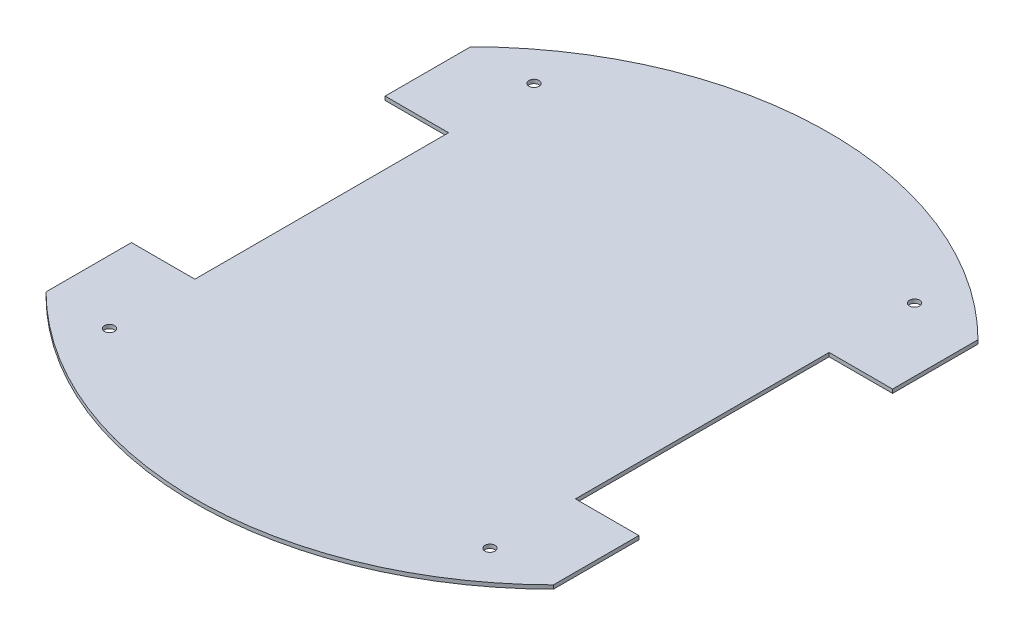
SolidWorks part; units mm, degrees
ref_plane "Front Plane" through (0, 0, 0) normal (0, 0, 1) x (1, 0, 0)
ref_plane "Top Plane" through (0, 0, 0) normal (0, 1, 0) x (1, 0, 0)
ref_plane "Right Plane" through (0, 0, 0) normal (1, 0, 0) x (0, 0, -1)
sketch "Sketch3" plane through (0, 0, 0) normal (0, 1, 0) x (1, 0, 0)
  line L0 (-150, 100) -> (-200, 100)
  line L5 (-200, 100) -> (-150, 100) construction
  line L7 (200, -100) -> (150, -100) construction
  line L8 (-150, 100) -> (-150, -100)
  line L10 (150, -100) -> (150, 100)
  line L11 (150, 100) -> (200, 100)
  line L12 (200, 100) -> (200, 167.3599)
  line L13 (-150, -100) -> (-200, -100)
  line L14 (-200, -100) -> (-200, -167.3599)
  line L15 (-200, 100) -> (-200, 167.3599)
  line L16 (150, -100) -> (200, -100)
  line L17 (200, -100) -> (200, -167.3599)
  line L18 (150, 100) -> (200, 100) construction
  line L19 (-150, -100) -> (-200, -100) construction
  arc A0 (-200, -167.3599) -> (200, -167.3599) centre (0, 33.3333) ccw
  arc A1 (-200, 167.3599) -> (200, 167.3599) centre (0, -33.3333) cw
  point P0 (0, 0)
extrude "Boss-Extrude1" add sketch "Sketch3" along normal blind 3
sketch "Sketch4" plane through (0, 3, 0) normal (0, 1, 0) x (1, 0, 0)
  line L0 (0, 250) -> (0, -250) construction
  line L1 (-150, 0) -> (150, 0) construction
  line L2 (-150, 100) -> (-150, -100) construction
  line L3 (150, -100) -> (150, 100) construction
  circle A0 centre (-150, 167.3599) radius 4
  arc A1 (200, 167.3599) -> (-200, 167.3599) centre (0, -33.3333) ccw construction
  arc A2 (-200, -167.3599) -> (200, -167.3599) centre (0, 33.3333) ccw construction
  circle A3 centre (150, 167.3599) radius 4
  circle A4 centre (150, -167.3599) radius 4
  circle A5 centre (-150, -167.3599) radius 4
extrude "Cut-Extrude1" cut sketch "Sketch4" against normal blind 10
